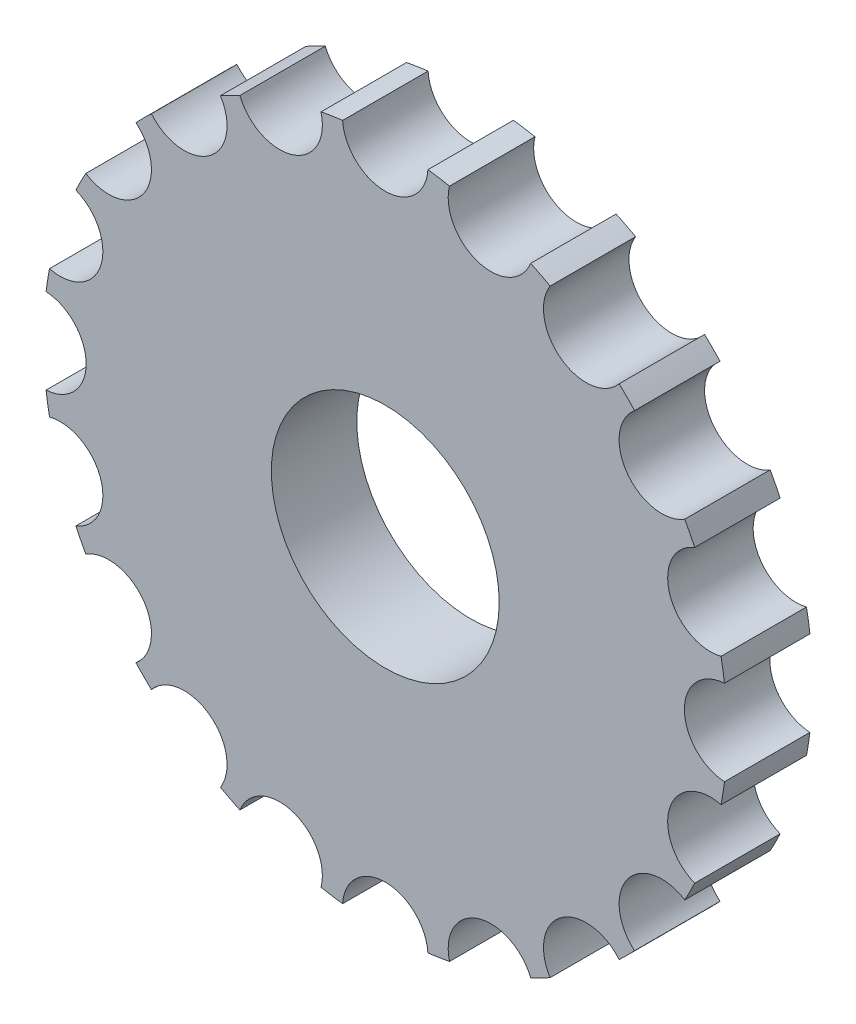
SolidWorks part; units mm, degrees
ref_plane "Front Plane" through (0, 0, 0) normal (0, 0, 1) x (1, 0, 0)
ref_plane "Top Plane" through (0, 0, 0) normal (0, 1, 0) x (1, 0, 0)
ref_plane "Right Plane" through (0, 0, 0) normal (1, 0, 0) x (0, 0, -1)
sketch "Sketch1" plane through (0, 0, 0) normal (0, 0, 1) x (1, 0, 0)
  circle A0 centre (0, 0) radius 60
  circle A1 centre (0, 0) radius 20
  dimension "D1" = 120
  dimension "D2" = 40
extrude "Boss-Extrude1" add sketch "Sketch1" along normal blind 15
sketch "Sketch2" plane through (0, 0, 15) normal (0, 0, 1) x (1, 0, 0)
  circle A0 centre (0, 60) radius 7.5
  circle A1 centre (0, 0) radius 60 construction
  circle A2 centre (18.541, 57.0634) radius 7.5
  circle A3 centre (35.2671, 48.541) radius 7.5
  circle A4 centre (48.541, 35.2671) radius 7.5
  circle A5 centre (57.0634, 18.541) radius 7.5
  circle A6 centre (60, 0) radius 7.5
  circle A7 centre (57.0634, -18.541) radius 7.5
  circle A8 centre (48.541, -35.2671) radius 7.5
  circle A9 centre (35.2671, -48.541) radius 7.5
  circle A10 centre (18.541, -57.0634) radius 7.5
  circle A11 centre (0, -60) radius 7.5
  circle A12 centre (-18.541, -57.0634) radius 7.5
  circle A13 centre (-35.2671, -48.541) radius 7.5
  circle A14 centre (-48.541, -35.2671) radius 7.5
  circle A15 centre (-57.0634, -18.541) radius 7.5
  circle A16 centre (-60, 0) radius 7.5
  circle A17 centre (-57.0634, 18.541) radius 7.5
  circle A18 centre (-48.541, 35.2671) radius 7.5
  circle A19 centre (-35.2671, 48.541) radius 7.5
  circle A20 centre (-18.541, 57.0634) radius 7.5
  point P45 (0, 0)
  dimension "D1" = 15
  dimension "D2" = 20
extrude "Cut-Extrude1" cut sketch "Sketch2" against normal blind 15
